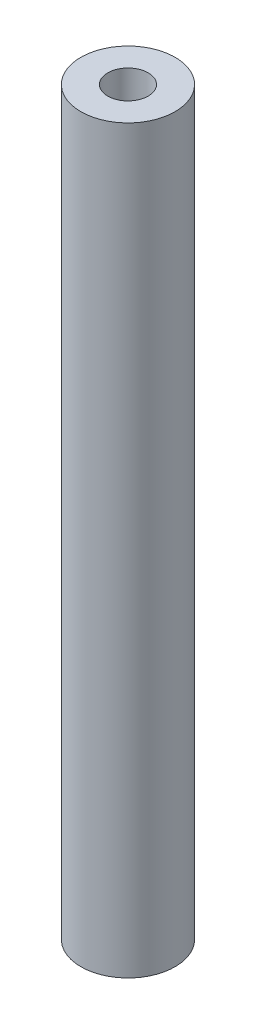
SolidWorks part; units mm, degrees
ref_plane "Front Plane" through (0, 0, 0) normal (0, 0, 1) x (1, 0, 0)
ref_plane "Top Plane" through (0, 0, 0) normal (0, 1, 0) x (1, 0, 0)
ref_plane "Right Plane" through (0, 0, 0) normal (1, 0, 0) x (0, 0, -1)
sketch "Sketch1" plane through (0, 0, 0) normal (0, 1, 0) x (1, 0, 0)
  circle A0 centre (0, 0) radius 1.5
  circle A1 centre (0, 0) radius 3.5
  dimension "D1" = 3
  dimension "D2" = 7
extrude "Boss-Extrude1" add sketch "Sketch1" along normal blind 55
